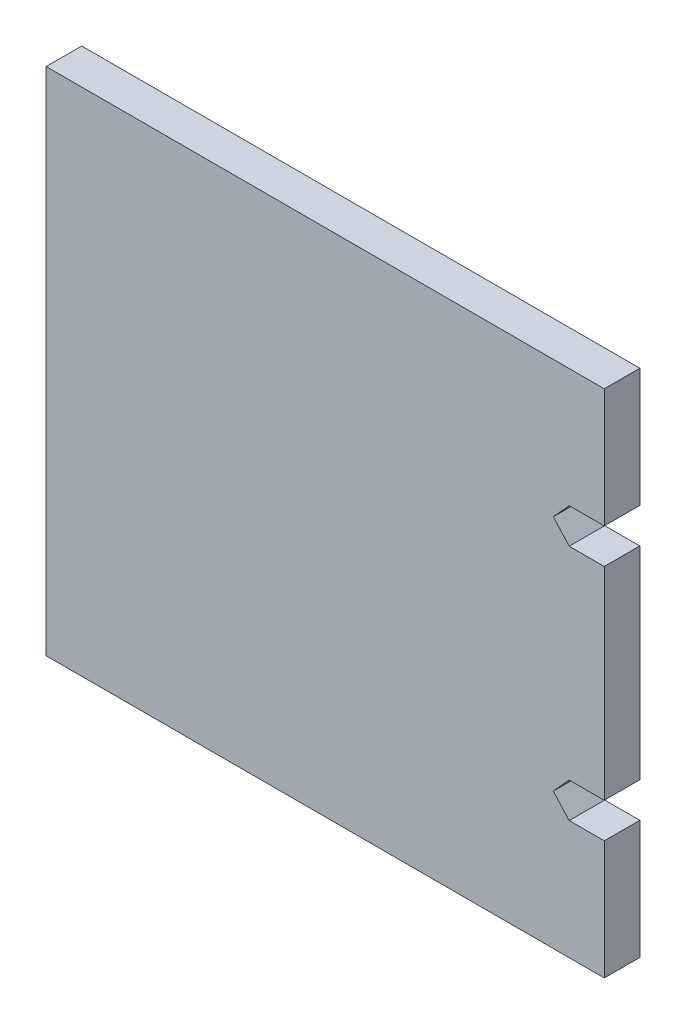
SolidWorks part; units mm, degrees
material "Plástico personalizado"
ref_plane "Plano frontal" through (0, 0, 0) normal (0, 0, 1) x (1, 0, 0)
ref_plane "Plano superior" through (0, 0, 0) normal (0, 1, 0) x (1, 0, 0)
ref_plane "Plano direito" through (0, 0, 0) normal (1, 0, 0) x (0, 0, -1)
sketch "Esboço1" plane through (0, 0, 0) normal (0, 0, 1) x (1, 0, 0)
  line L1 (0, 0) -> (350, 0)
  line L2 (0, 0) -> (0, 320)
  line L3 (0, 320) -> (350, 320)
  line L4 (350, 0) -> (350, 320)
  dimension "D1" = 320
  dimension "D2" = 350
extrude "Ressalto-extrusão1" add sketch "Esboço1" along normal blind 22.3
sketch "Esboço2" plane through (0, 0, 22.3) normal (0, 0, 1) x (1, 0, 0)
  line L0 (0, 0) -> (350, 0) construction
  line L1 (350, 234.5) -> (318, 234.5) construction
  line L2 (318, 234.5) -> (328, 223.5)
  line L3 (350, 223.5) -> (328, 223.5)
  line L4 (350, 245.5) -> (350, 223.5)
  line L5 (350, 245.5) -> (328, 245.5)
  line L6 (175, 320) -> (175, 0) construction
  line L7 (350, 320) -> (0, 320) construction
  line L8 (328, 245.5) -> (318, 234.5)
  line L13 (0, 320) -> (0, 0) construction
  line L18 (350, 0) -> (350, 320) construction
  line L19 (328, 74.5) -> (318, 85.5)
  line L20 (350, 74.5) -> (328, 74.5)
  line L21 (350, 74.5) -> (350, 96.5)
  line L22 (350, 96.5) -> (328, 96.5)
  line L24 (318, 85.5) -> (328, 96.5)
  line L25 (350, 85.5) -> (318, 85.5) construction
  line L26 (350, 160) -> (0, 160) construction
  dimension "D1" = 22
  dimension "D6" = 32
  dimension "D7" = 74.5
  dimension "D8" = 22
extrude "Corte-extrusão1" cut sketch "Esboço2" against normal through all
